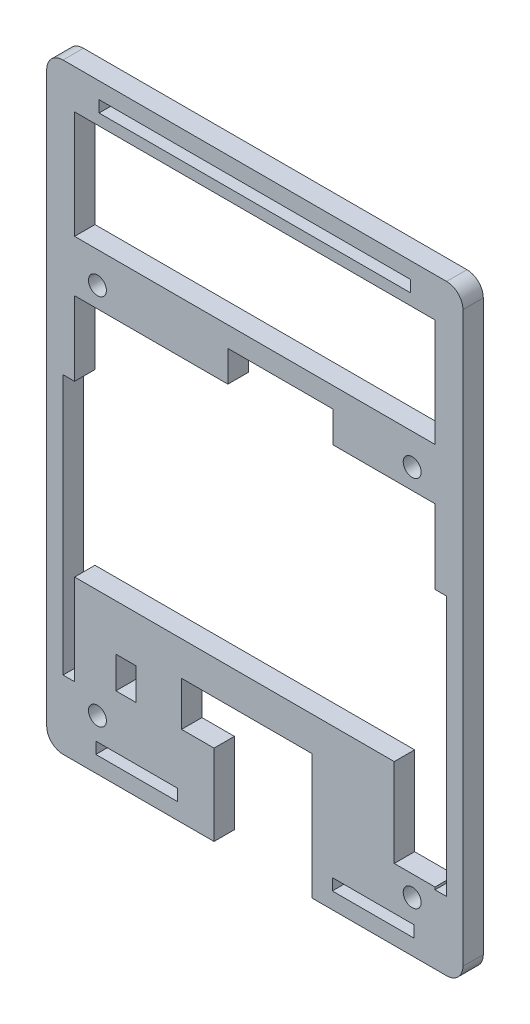
SolidWorks part; units mm, degrees
ref_plane "Front Plane" through (0, 0, 0) normal (0, 0, 1) x (1, 0, 0)
ref_plane "Top Plane" through (0, 0, 0) normal (0, 1, 0) x (1, 0, 0)
ref_plane "Right Plane" through (0, 0, 0) normal (1, 0, 0) x (0, 0, -1)
sketch "Sketch1" plane through (0, 0, 0) normal (0, 0, 1) x (1, 0, 0)
  line L0 (36.9824, 0) -> (36.9824, 15.1384)
  line L1 (52.832, 0) -> (40.132, 0) construction
  line L2 (36.9824, 15.1384) -> (16.6624, 15.1384)
  line L3 (16.6624, 15.1384) -> (16.6624, 8.255)
  line L4 (16.6624, 8.255) -> (21.717, 8.255)
  line L5 (21.717, 8.255) -> (21.717, 0)
  line L6 (40.132, 0) -> (16.002, 0) construction
  line L8 (0, 20.4724) -> (49.784, 20.4724)
  line L9 (49.784, 20.4724) -> (49.784, 6.731)
  line L10 (49.784, 6.731) -> (56.134, 6.731)
  line L11 (52.578, 6.731) -> (56.134, 6.731) construction
  line L12 (16.002, 0) -> (3.302, 0) construction
  line L13 (6.4262, 13.2842) -> (9.6012, 13.2842)
  line L14 (6.4262, 13.2842) -> (6.4262, 8.3312)
  line L15 (6.4262, 8.3312) -> (9.6012, 8.3312)
  line L16 (9.6012, 13.2842) -> (9.6012, 8.3312)
  line L17 (0, 6.35) -> (0, -1.8034) construction
  line L18 (0, 6.35) -> (0, 46.863) construction
  line L19 (16.002, -1.8034) -> (16.002, 0) construction
  line L20 (16.002, -1.8034) -> (3.302, -1.8034) construction
  line L21 (3.302, -1.8034) -> (3.302, 0) construction
  line L22 (40.132, -1.8034) -> (40.132, 0) construction
  line L23 (52.832, -1.8034) -> (40.132, -1.8034) construction
  line L24 (52.832, -1.8034) -> (52.832, 0) construction
  line L25 (57.9374, 6.35) -> (56.134, 6.35) construction
  line L28 (57.9374, 46.863) -> (56.134, 46.863) construction
  line L29 (-1.8034, 46.863) -> (0, 46.863) construction
  line L30 (-1.8034, 6.35) -> (-1.8034, 46.863) construction
  line L31 (-1.8034, 6.35) -> (0, 6.35) construction
  line L32 (16.002, -1.8034) -> (16.002, 0)
  line L33 (16.002, -1.8034) -> (3.302, -1.8034)
  line L34 (3.302, -1.8034) -> (3.302, 0)
  line L35 (16.002, 0) -> (3.302, 0)
  line L36 (40.132, -1.8034) -> (40.132, 0)
  line L37 (52.832, -1.8034) -> (40.132, -1.8034)
  line L38 (52.832, 0) -> (40.132, 0)
  line L39 (52.832, -1.8034) -> (52.832, 0)
  line L40 (57.9374, 6.35) -> (56.134, 6.35)
  line L41 (57.9374, 46.863) -> (57.9374, 6.35)
  line L42 (56.134, 46.863) -> (56.134, 6.35)
  line L43 (57.9374, 46.863) -> (56.134, 46.863)
  line L44 (-1.8034, 46.863) -> (0, 46.863)
  line L45 (0, 6.35) -> (0, 46.863)
  line L46 (-1.8034, 6.35) -> (-1.8034, 46.863)
  line L47 (-1.8034, 6.35) -> (0, 6.35)
  line L48 (57.9374, -4.3434) -> (-1.8034, -4.3434) construction
  line L49 (57.9374, -4.3434) -> (-1.8034, -4.3434)
  line L50 (-4.3434, -1.8034) -> (-4.3434, 86.7664)
  line L51 (60.4774, -1.8034) -> (60.4774, 86.7664)
  line L52 (0, 66.421) -> (56.134, 66.421)
  line L53 (3.556, 58.42) -> (0, 58.42) construction
  line L54 (52.578, 58.42) -> (56.134, 58.42) construction
  line L55 (3.556, 58.42) -> (0, 58.42)
  line L56 (52.578, 58.42) -> (56.134, 58.42)
  line L57 (3.556, 58.42) -> (23.876, 58.42)
  line L58 (23.876, 58.42) -> (23.876, 63.246)
  line L59 (23.876, 63.246) -> (40.259, 63.246)
  line L60 (40.259, 63.246) -> (40.259, 58.42)
  line L61 (40.259, 58.42) -> (52.578, 58.42)
  line L63 (-1.8034, 89.3064) -> (57.9374, 89.3064)
  line L64 (0, 83.2104) -> (56.134, 83.2104)
  line L67 (0, 46.863) -> (0, 83.2104)
  line L68 (56.134, 83.2104) -> (56.134, 46.863)
  line L69 (0, 83.2104) -> (0, 46.863)
  line L70 (3.81, 86.7664) -> (52.324, 86.7664)
  line L71 (3.81, 86.7664) -> (3.81, 84.963)
  line L72 (3.81, 84.963) -> (52.324, 84.963)
  line L73 (52.324, 86.7664) -> (52.324, 84.963)
  line L74 (56.134, 83.2104) -> (56.134, 46.863)
  line L76 (36.9824, 0) -> (36.9824, -4.3434)
  line L77 (21.717, 0) -> (21.717, -4.3434)
  circle A0 centre (3.556, 3.556) radius 1.397 construction
  circle A1 centre (52.578, 3.556) radius 1.397 construction
  circle A2 centre (3.556, 61.595) radius 1.397 construction
  circle A3 centre (52.578, 61.595) radius 1.397 construction
  circle A4 centre (3.556, 3.556) radius 1.397
  circle A5 centre (52.578, 3.556) radius 1.397
  circle A6 centre (3.556, 61.595) radius 1.397
  circle A7 centre (52.578, 61.595) radius 1.397
  arc A8 (-4.3434, -1.8034) -> (-1.8034, -4.3434) centre (-1.8034, -1.8034) ccw construction
  arc A9 (57.9374, -4.3434) -> (60.4774, -1.8034) centre (57.9374, -1.8034) ccw construction
  arc A10 (-4.3434, -1.8034) -> (-1.8034, -4.3434) centre (-1.8034, -1.8034) ccw
  arc A11 (57.9374, -4.3434) -> (60.4774, -1.8034) centre (57.9374, -1.8034) ccw
  arc A12 (57.9374, 89.3064) -> (60.4774, 86.7664) centre (57.9374, 86.7664) cw
  arc A13 (-4.3434, 86.7664) -> (-1.8034, 89.3064) centre (-1.8034, 86.7664) cw
  point P74 (-4.3434, 89.3064)
  dimension "D12" = 3.429
  dimension "D17" = 2.54
  dimension "D1" = 20.32
  dimension "D3" = 15.2654
  dimension "D4" = 8.255
  dimension "D5" = 19.4818
  dimension "D6" = 5.334
  dimension "D7" = 3.175
  dimension "D8" = 4.953
  dimension "D9" = 8.3312
  dimension "D10" = 6.4262
  dimension "D11" = 6.35
  dimension "D13" = 23.495
  dimension "D14" = 23.876
  dimension "D15" = 3.175
  dimension "D16" = 1.8034
  dimension "D18" = 3.556
  dimension "D19" = 3.81
  dimension "D20" = 3.81
  dimension "D21" = 15.875
  dimension "D22" = 16.7894
extrude "Boss-Extrude1" add sketch "Sketch1" along normal blind 3.175
